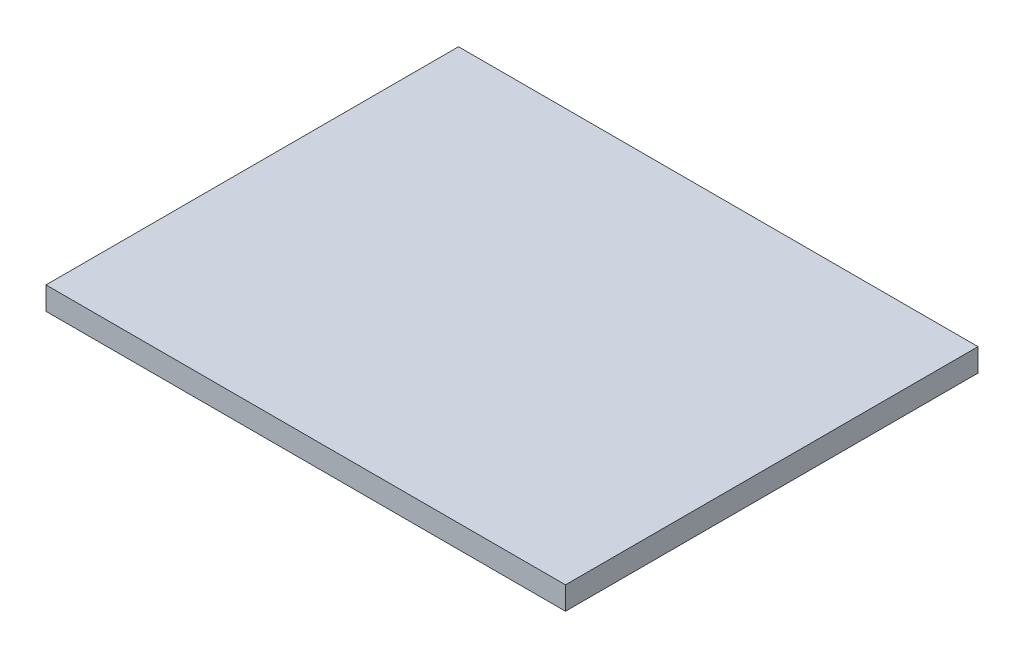
SolidWorks part; units mm, degrees
ref_plane "Front Plane" through (0, 0, 0) normal (0, 0, 1) x (1, 0, 0)
ref_plane "Top Plane" through (0, 0, 0) normal (0, 1, 0) x (1, 0, 0)
ref_plane "Right Plane" through (0, 0, 0) normal (1, 0, 0) x (0, 0, -1)
sketch "Sketch1" plane through (0, 0, 0) normal (0, 1, 0) x (1, 0, 0)
  line L0 (31, 24) -> (-31, 24)
  line L1 (34, -27) -> (-34, -27)
  line L2 (34, -27) -> (34, 27)
  line L3 (34, 27) -> (-34, 27)
  line L4 (-34, -27) -> (-34, 27)
  line L5 (0, 27) -> (0, -27) construction
  line L6 (34, 0) -> (-34, 0) construction
  line L7 (-31, -24) -> (-31, 24)
  line L8 (31, -24) -> (-31, -24)
  line L9 (31, -24) -> (31, 24)
  line L10 (-31, 24) -> (-34, 27)
  line L11 (31, 24) -> (34, 27)
  line L12 (34, -27) -> (31, -24)
  line L13 (-31, -24) -> (-34, -27)
  point P0 (0, 0)
  dimension "D1" = 68
  dimension "D2" = 54
  dimension "D3" = 3
extrude "Boss-Extrude1" add sketch "Sketch1" along normal blind 3 contours L8 L9 L0 L7 | L0 L11 L3 L10 | L13 L7 L10 L4 | L8 L13 L1 L12 | L12 L2 L11 L9
